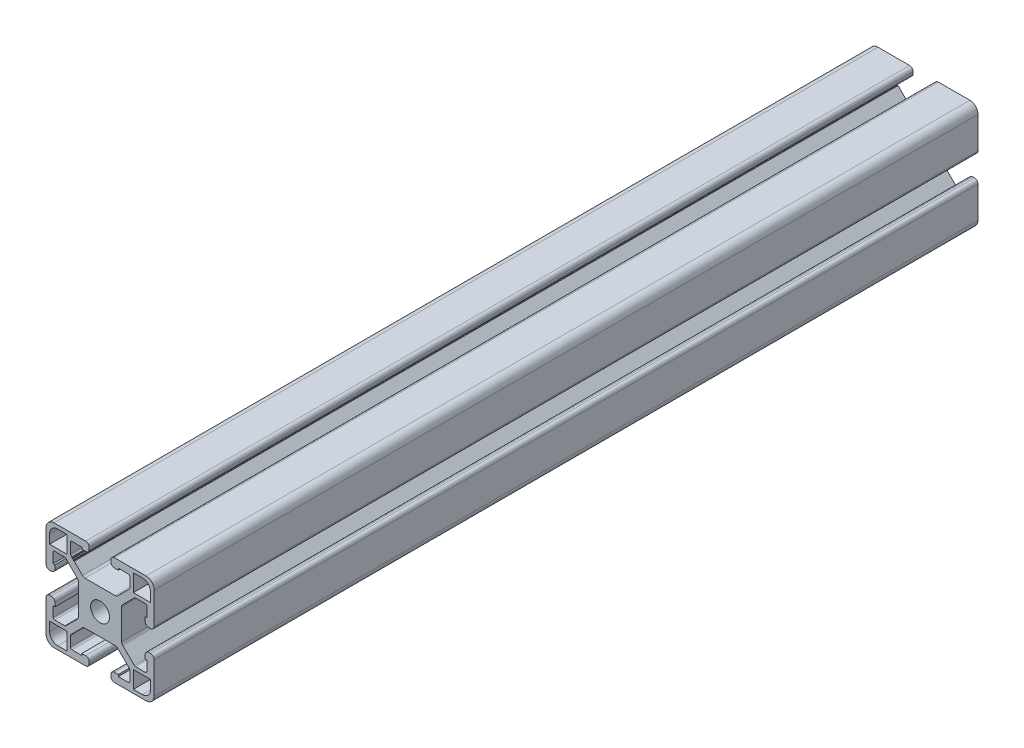
SolidWorks part; units mm, degrees
ref_plane "Front Plane" through (0, 0, 0) normal (0, 0, 1) x (1, 0, 0)
ref_plane "Top Plane" through (0, 0, 0) normal (0, 1, 0) x (1, 0, 0)
ref_plane "Right Plane" through (0, 0, 0) normal (1, 0, 0) x (0, 0, -1)
sketch "Sketch2" plane through (0, 0, 0) normal (0, 0, 1) x (1, 0, 0)
  line L0 (0, 20) -> (0, -20) construction
  line L1 (-20, 0) -> (20, 0) construction
  line L2 (4, -20) -> (20, -20)
  line L3 (20, -20) -> (20, -4)
  line L5 (6.75, -17.36) -> (10.4, -17.36)
  line L7 (0, 0) -> (20, -20) construction
  line L9 (17.36, -6.75) -> (17.36, -10.4)
  line L11 (10.4334, -8.5666) -> (8.5666, -10.4334) construction
  line L12 (11, -16.76) -> (11, -12.8668)
  line L13 (6.1332, -8) -> (11, -12.8668)
  line L14 (16.76, -11) -> (12.8668, -11)
  line L15 (8, -6.1332) -> (12.8668, -11)
  line L16 (4, -20) -> (4, -16.7)
  line L18 (4, -16.7) -> (6.75, -16.7)
  line L19 (6.75, -16.7) -> (6.75, -17.36)
  line L20 (20, -4) -> (16.7, -4)
  line L21 (16.7, -4) -> (16.7, -6.75)
  line L22 (16.7, -6.75) -> (17.36, -6.75)
  line L23 (6.75, -17.36) -> (6.75, -20) construction
  circle A0 centre (0, 0) radius 3.5
  arc A1 (10.4, -17.36) -> (11, -16.76) centre (10.4, -16.76) ccw
  arc A2 (17.36, -10.4) -> (16.76, -11) centre (16.76, -10.4) cw
  point P8 (0, -8)
  point P16 (9.5, -9.5)
  dimension "Center Hole Diameter" = 7
  dimension "D3" = 0.6
  dimension "Rail Height" = 40
  dimension "Rail Width" = 40
  dimension "T-Slot Width" = 8
  dimension "Slot Depth" = 12
  dimension "Inner Slot Width" = 22
  dimension "D1" = 2.75
  dimension "D2" = 3.3
  dimension "D4" = 0.66
sketch "Sketch3" plane through (0, 0, 0) normal (1, 0, 0) x (0, 0, -1)
  line L0 (-152.4, -20) -> (152.4, -20) construction
  line L1 (-127, 0) -> (127, 0) construction
  dimension "Length" = 304.8
  dimension "D1" = 25.4
sketch "Sketch4" plane through (0, 0, 0) normal (0, 0, 1) x (1, 0, 0)
  line L1 (20, -17) -> (20, -5.32)
  line L2 (20, -4) -> (16.7, -4) construction
  line L3 (16.7, -4) -> (16.7, -6.75) construction
  line L7 (18.02, -4) -> (18.68, -4)
  line L9 (16.7, -5.32) -> (16.7, -6.75)
  line L10 (16.7, -6.75) -> (17.36, -6.75)
  line L11 (17.36, -6.75) -> (17.36, -10.4)
  line L13 (16.76, -11) -> (13.1153, -11)
  line L18 (16.76, -11) -> (12.8668, -11) construction
  line L20 (8, -6.1332) -> (12.8668, -11) construction
  line L22 (4, -20) -> (20, -20) construction
  line L23 (20, -20) -> (20, -4) construction
  line L24 (17, -20) -> (5.32, -20)
  line L25 (4, -18.02) -> (4, -18.68)
  line L26 (4, -20) -> (4, -16.7) construction
  line L27 (4, -16.7) -> (6.75, -16.7) construction
  line L28 (5.32, -16.7) -> (6.75, -16.7)
  line L29 (6.75, -16.7) -> (6.75, -17.36)
  line L30 (6.75, -17.36) -> (10.4, -17.36)
  line L31 (6.1332, -8) -> (11, -12.8668) construction
  line L32 (11, -16.76) -> (11, -12.8668) construction
  line L33 (11, -13.1153) -> (11, -16.76)
  line L34 (0, -8) -> (5.5865, -8)
  line L35 (6.5199, -8.3866) -> (10.8243, -12.691)
  line L36 (12.691, -10.8243) -> (8.3866, -6.5199)
  line L37 (8, 0) -> (8, -5.5865)
  line L38 (-20, 0) -> (20, 0) construction
  line L39 (15.68, -18.68) -> (12.32, -18.68)
  line L40 (12.32, -18.68) -> (12.32, -12.32)
  line L41 (18.68, -12.32) -> (18.68, -15.68)
  line L42 (12.32, -12.32) -> (18.68, -12.32)
  line L43 (0, 0) -> (20, -20) construction
  line L44 (12.32, -18.68) -> (12.32, -20) construction
  line L45 (11, -14.9376) -> (12.32, -14.9376) construction
  line L46 (0, -8) -> (0, -3.5)
  line L47 (8, 0) -> (3.5, 0)
  arc A1 (18.68, -4) -> (20, -5.32) centre (18.68, -5.32) cw
  arc A10 (16.7, -5.32) -> (18.02, -4) centre (18.02, -5.32) cw
  arc A12 (17, -20) -> (20, -17) centre (17, -17) ccw
  arc A13 (4, -18.02) -> (5.32, -16.7) centre (5.32, -18.02) cw
  arc A14 (4, -18.68) -> (5.32, -20) centre (5.32, -18.68) ccw
  arc A15 (10.4, -17.36) -> (11, -16.76) centre (10.4, -16.76) ccw construction
  arc A16 (10.4, -17.36) -> (11, -16.76) centre (10.4, -16.76) ccw
  arc A17 (10.8243, -12.691) -> (11, -13.1153) centre (10.4, -13.1153) cw
  arc A18 (5.5865, -8) -> (6.5199, -8.3866) centre (5.5865, -9.32) cw
  arc A19 (16.76, -11) -> (17.36, -10.4) centre (16.76, -10.4) ccw construction
  arc A20 (16.76, -11) -> (17.36, -10.4) centre (16.76, -10.4) ccw
  arc A21 (12.691, -10.8243) -> (13.1153, -11) centre (13.1153, -10.4) ccw
  arc A22 (8, -5.5865) -> (8.3866, -6.5199) centre (9.32, -5.5865) ccw
  arc A23 (18.68, -15.68) -> (15.68, -18.68) centre (15.68, -15.68) cw
  circle A24 centre (0, 0) radius 3.5 construction
  arc A25 (0, -3.5) -> (3.5, 0) centre (0, 0) ccw
  point P74 (4, -18.35)
  dimension "D2" = 1.32
  dimension "D1" = 1.32
  dimension "D3" = 3
  dimension "D4" = 3
extrude "Boss-Extrude1" add sketch "Sketch4" along normal mid plane 304.8
mirror "Mirror1" about plane through (0, 0, 0) normal (1, 0, 0) of bodies 134
mirror "Mirror2" about plane through (0, 0, 0) normal (0, 1, 0) of bodies 135
sketch "Sketch5" plane through (0, 0, 0) normal (0, 0, 1) x (1, 0, 0)
  line L1 (-10.4532, 12.32) -> (-10.4532, 11.99)
  line L2 (-6.5199, 8.3866) -> (-10.8243, 12.691) construction
  line L3 (-10.4532, 11.99) -> (-10.1232, 11.99)
  line L4 (-10.1232, 11.99) -> (-9.8899, 11.7567)
  line L5 (-9.8899, 11.7567) -> (-9.8899, 11.4267)
  line L6 (-9.8899, 11.4267) -> (-9.5599, 11.4267)
  line L7 (-10.4532, 12.32) -> (-9.5599, 12.32)
  line L8 (-9.5599, 12.32) -> (-9.5599, 11.4267)
  dimension "D1" = 0.33
extrude "Cut-Extrude1" cut sketch "Sketch5" against normal through all both and the other way through all
equation "\"D3@Sketch2\"=\"T-Slot Width@Sketch2\"*0.075"
equation "\"D1@Boss-Extrude1\"=\"Length@Sketch3\""
equation "\"D1@Sketch2\"=\"Inner Slot Width@Sketch2\"*0.125"
equation "\"D2@Sketch2\"=\"Slot Depth@Sketch2\"*0.275"
equation "\"D4@Sketch2\"=\"D2@Sketch2\"*0.2"
equation "\"D1@Sketch4\"=\"D2@Sketch2\"*0.4"
equation "\"D2@Sketch4\"=\"D1@Sketch4\""
equation "\"D3@Sketch4\"=\"Rail Height@Sketch2\"*0.075"
equation "\"D4@Sketch4\"=\"Rail Height@Sketch2\"*0.075"
equation "\"D1@Sketch5\"=\"D4@Sketch2\"*0.5"
